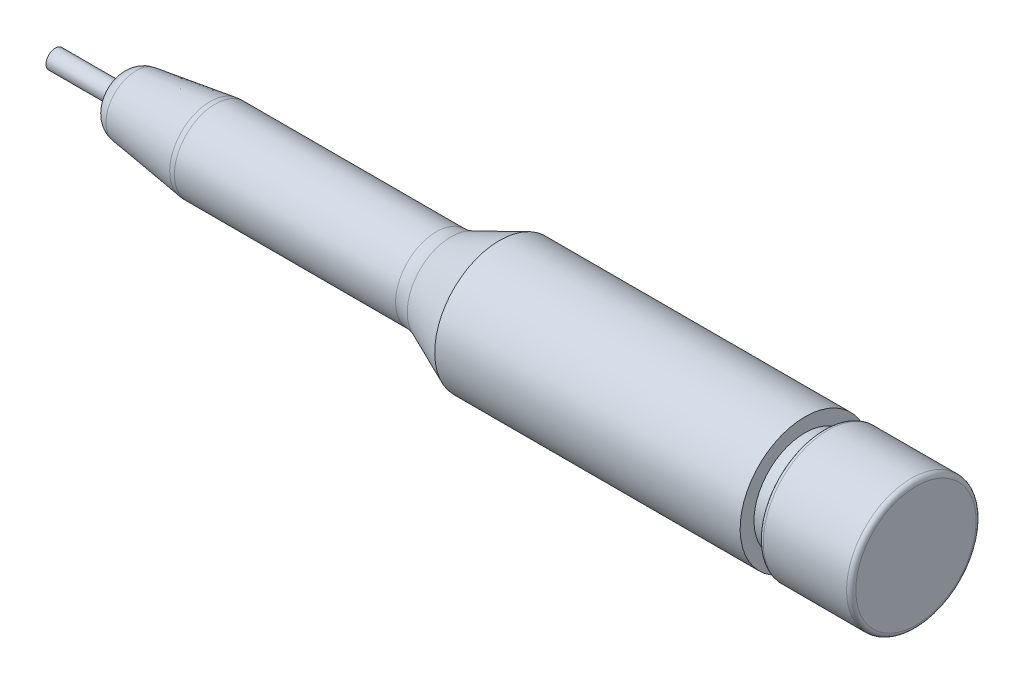
SolidWorks part; units mm, degrees
ref_plane "Plano frontal" through (0, 0, 0) normal (0, 0, 1) x (1, 0, 0)
ref_plane "Plano superior" through (0, 0, 0) normal (0, 1, 0) x (1, 0, 0)
ref_plane "Plano direito" through (0, 0, 0) normal (1, 0, 0) x (0, 0, -1)
sketch "Esboço1" plane through (0, 0, 0) normal (0, 0, 1) x (1, 0, 0)
  line L0 (0, 0) -> (0, 1)
  line L1 (0, 1) -> (7, 1)
  line L2 (7, 1) -> (7, 3)
  line L3 (7, 3) -> (17, 4.4)
  line L4 (17, 4.4) -> (42, 4.4)
  line L5 (42, 4.4) -> (48, 7)
  line L6 (48, 7) -> (81, 7)
  line L7 (81, 7) -> (81, 5.5)
  line L8 (81, 5.5) -> (83, 5.5)
  line L9 (83, 5.5) -> (83, 7)
  line L10 (83, 7) -> (93, 7)
  line L11 (93, 7) -> (93, 0)
  line L12 (93, 0) -> (0, 0)
  dimension "D1" = 2
  dimension "D2" = 2
  dimension "D3" = 33
  dimension "D4" = 6
  dimension "D5" = 10
  dimension "D6" = 93
  dimension "D7" = 7
  dimension "D8" = 10
  dimension "D10" = 7
  dimension "D11" = 4.4
  dimension "D12" = 1
  dimension "D13" = 1.5
  dimension "D14" = 3
revolve "Revolução1" add sketch "Esboço1" angle 360 about L12
cosmetic thread "Representação de rosca1"
cosmetic thread "Representação de rosca2"
cosmetic thread "Representação de rosca3"
fillet "Filete1" radius 2 1 edges at (7, 3, 0)
fillet "Filete2" radius 4 2 edges at (42, 4.4, 0) (17, 4.4, 0)
fillet "Filete3" radius 0.5 2 edges at (93, 7, 0) (83, 7, 0)
